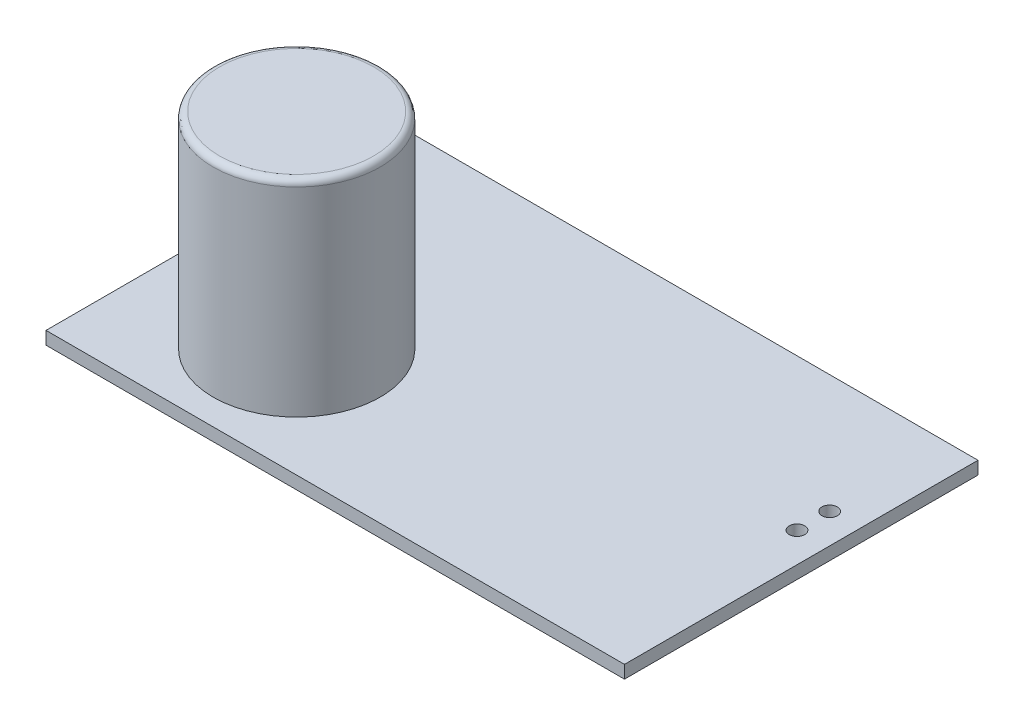
SolidWorks part; units mm, degrees
ref_plane "Спереди" through (0, 0, 0) normal (0, 0, 1) x (1, 0, 0)
ref_plane "Сверху" through (0, 0, 0) normal (0, 1, 0) x (1, 0, 0)
ref_plane "Справа" through (0, 0, 0) normal (1, 0, 0) x (0, 0, -1)
sketch "Эскиз1" plane through (0, 0, 0) normal (0, 1, 0) x (1, 0, 0)
  line L1 (0, 0) -> (45, 0)
  line L2 (0, 0) -> (0, 27.5)
  line L3 (0, 27.5) -> (45, 27.5)
  line L4 (45, 0) -> (45, 27.5)
  dimension "D1" = 27.5
  dimension "D2" = 45
extrude "Бобышка-Вытянуть1" add sketch "Эскиз1" along normal blind 1
sketch "Эскиз2" plane through (0, 1, 0) normal (0, 1, 0) x (1, 0, 0)
  line L1 (0, 27.5) -> (0, 0) construction
  line L2 (0, 0) -> (45, 0) construction
  circle A0 centre (11, 8.5) radius 6.5
  point P2 (4.5, 8.5)
  point P3 (11, 2)
  dimension "D1" = 13
  dimension "D2" = 4.5
  dimension "D3" = 2
extrude "Бобышка-Вытянуть2" add sketch "Эскиз2" along normal blind 16 separate body
fillet "Скругление1" radius 0.5 1 edges at (11, 17, -2)
sketch "Эскиз4" plane through (0, 1, 0) normal (0, 1, 0) x (1, 0, 0)
  line L0 (0, 0) -> (0, 27.432)
  line L1 (0, 27.432) -> (44.958, 27.432)
  line L2 (44.958, 27.432) -> (44.958, 0)
  line L3 (44.958, 0) -> (0, 0)
  line L4 (2.8448, 11.684) -> (1.2192, 11.684)
  line L5 (2.8448, 11.684) -> (1.2192, 11.684)
  line L6 (2.8448, 14.224) -> (1.2192, 14.224)
  line L7 (2.8448, 14.224) -> (1.2192, 14.224)
  line L8 (41.8592, 18.288) -> (43.4848, 18.288)
  line L9 (41.8592, 18.288) -> (43.4848, 18.288)
  line L10 (41.8592, 15.748) -> (43.4848, 15.748)
  line L11 (41.8592, 15.748) -> (43.4848, 15.748)
  arc A0 (0, 27.432) -> (-0.0254, 27.432) centre (-0.0127, 27.432) ccw
  arc A1 (0, 0) -> (0.0254, 0) centre (0.0127, 0) ccw
  arc A2 (44.958, 27.432) -> (44.958, 27.4574) centre (44.958, 27.4447) ccw
  arc A3 (0, 27.432) -> (0, 27.4066) centre (0, 27.4193) ccw
  arc A4 (44.958, 0) -> (44.9834, 0) centre (44.9707, 0) ccw
  arc A5 (44.958, 27.432) -> (44.9326, 27.432) centre (44.9453, 27.432) ccw
  arc A6 (0, 0) -> (0, -0.0254) centre (0, -0.0127) ccw
  arc A7 (44.958, 0) -> (44.958, 0.0254) centre (44.958, 0.0127) ccw
  arc A8 (1.2192, 12.0904) -> (1.2192, 11.2776) centre (1.2192, 11.684) ccw
  arc A9 (2.8448, 11.2776) -> (2.8448, 12.0904) centre (2.8448, 11.684) ccw
  arc A10 (1.2192, 12.0904) -> (1.2192, 11.2776) centre (1.2192, 11.684) ccw
  arc A11 (2.8448, 11.2776) -> (2.8448, 12.0904) centre (2.8448, 11.684) ccw
  arc A12 (1.2192, 14.6304) -> (1.2192, 13.8176) centre (1.2192, 14.224) ccw
  arc A13 (2.8448, 13.8176) -> (2.8448, 14.6304) centre (2.8448, 14.224) ccw
  arc A14 (1.2192, 14.6304) -> (1.2192, 13.8176) centre (1.2192, 14.224) ccw
  arc A15 (2.8448, 13.8176) -> (2.8448, 14.6304) centre (2.8448, 14.224) ccw
  arc A16 (43.4848, 17.8816) -> (43.4848, 18.6944) centre (43.4848, 18.288) ccw
  arc A17 (41.8592, 18.6944) -> (41.8592, 17.8816) centre (41.8592, 18.288) ccw
  arc A18 (43.4848, 17.8816) -> (43.4848, 18.6944) centre (43.4848, 18.288) ccw
  arc A19 (41.8592, 18.6944) -> (41.8592, 17.8816) centre (41.8592, 18.288) ccw
  arc A20 (43.4848, 15.3416) -> (43.4848, 16.1544) centre (43.4848, 15.748) ccw
  arc A21 (41.8592, 16.1544) -> (41.8592, 15.3416) centre (41.8592, 15.748) ccw
  arc A22 (43.4848, 15.3416) -> (43.4848, 16.1544) centre (43.4848, 15.748) ccw
  arc A23 (41.8592, 16.1544) -> (41.8592, 15.3416) centre (41.8592, 15.748) ccw
sketch "Эскиз5" plane through (0, 1, 0) normal (0, 1, 0) x (1, 0, 0)
  line L0 (2.8448, 14.224) -> (1.2192, 14.224) construction
  line L1 (2.8448, 11.684) -> (1.2192, 11.684) construction
  line L2 (41.8592, 18.288) -> (43.4848, 18.288) construction
  line L3 (41.8592, 15.748) -> (43.4848, 15.748) construction
  circle A0 centre (2.032, 14.224) radius 0.6
  circle A1 centre (2.032, 11.684) radius 0.6
  circle A2 centre (42.672, 18.288) radius 0.6
  circle A3 centre (42.672, 15.748) radius 0.6
  dimension "D1" = 1.2
extrude "Вырез-Вытянуть1" cut sketch "Эскиз5" against normal through all
